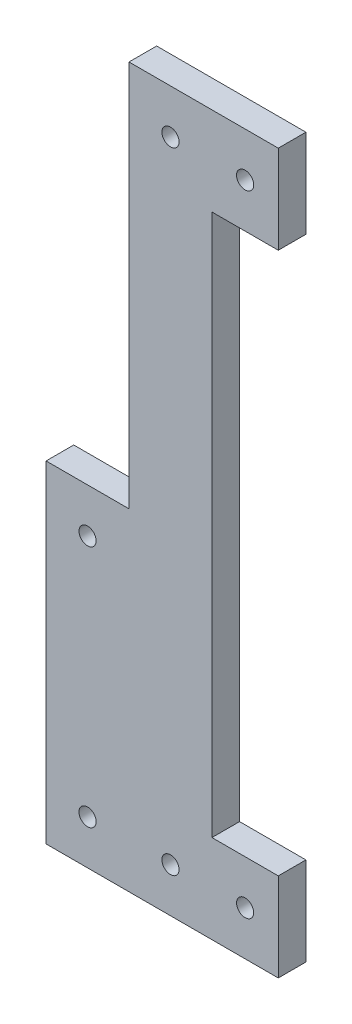
SolidWorks part; units mm, degrees
ref_plane "Front" through (0, 0, 0) normal (0, 0, 1) x (1, 0, 0)
ref_plane "Top" through (0, 0, 0) normal (0, 1, 0) x (1, 0, 0)
ref_plane "Right" through (0, 0, 0) normal (1, 0, 0) x (0, 0, -1)
sketch "Sketch1" plane through (0, 0, 0) normal (0, 0, 1) x (1, 0, 0)
  line L1 (0, 0) -> (15, 0)
  line L2 (0, 0) -> (0, 60)
  line L3 (0, 60) -> (15, 60)
  line L4 (15, 0) -> (15, 60)
  line L5 (0, 0) -> (15, 60) construction
  line L6 (0, 60) -> (15, 0) construction
  line L7 (15, 0) -> (30, 0)
  line L8 (15, 0) -> (15, 130)
  line L9 (15, 130) -> (30, 130)
  line L10 (30, 0) -> (30, 130)
  line L11 (15, 0) -> (30, 130) construction
  line L12 (15, 130) -> (30, 0) construction
  line L13 (30, 130) -> (42, 130)
  line L14 (30, 130) -> (30, 114)
  line L15 (30, 114) -> (42, 114)
  line L16 (42, 130) -> (42, 114)
  line L17 (30, 130) -> (42, 114) construction
  line L18 (30, 114) -> (42, 130) construction
  line L19 (30, 0) -> (42, 0)
  line L20 (30, 0) -> (30, 16)
  line L21 (30, 16) -> (42, 16)
  line L22 (42, 0) -> (42, 16)
  line L23 (30, 0) -> (42, 16) construction
  line L24 (30, 16) -> (42, 0) construction
  circle A0 centre (7.5, 52) radius 1.55
  circle A1 centre (7.5, 8) radius 1.55
  circle A2 centre (22.5, 122) radius 1.55
  circle A3 centre (22.5, 8) radius 1.55
  circle A4 centre (36, 122) radius 1.55
  circle A5 centre (36, 8) radius 1.55
  point P4 (7.5, 30)
  point P9 (22.5, 65)
  point P14 (7.5, 60)
  point P22 (36, 122)
  point P26 (36, 8)
  dimension "D5" = 3.1
  dimension "D6" = 3.1
  dimension "D7" = 8
  dimension "D8" = 8
  dimension "D9" = 3.1
  dimension "D10" = 3.1
  dimension "D15" = 3.1
  dimension "D16" = 6
  dimension "D17" = 3.1
  dimension "D18" = 6
  dimension "D1" = 60
  dimension "D2" = 15
  dimension "D3" = 130
  dimension "D4" = 15
  dimension "D11" = 8
  dimension "D12" = 8
  dimension "D13" = 12
  dimension "D14" = 16
  dimension "D19" = 16
  dimension "D20" = 12
extrude "Boss-Extrude1" add sketch "Sketch1" along normal blind 5 contours L1 L4 L3 L2 A1 A0 | L7 L10 L9 L8 L4 A3 A2 | L16 L13 L10 L15 | L19 L22 L21 L10
